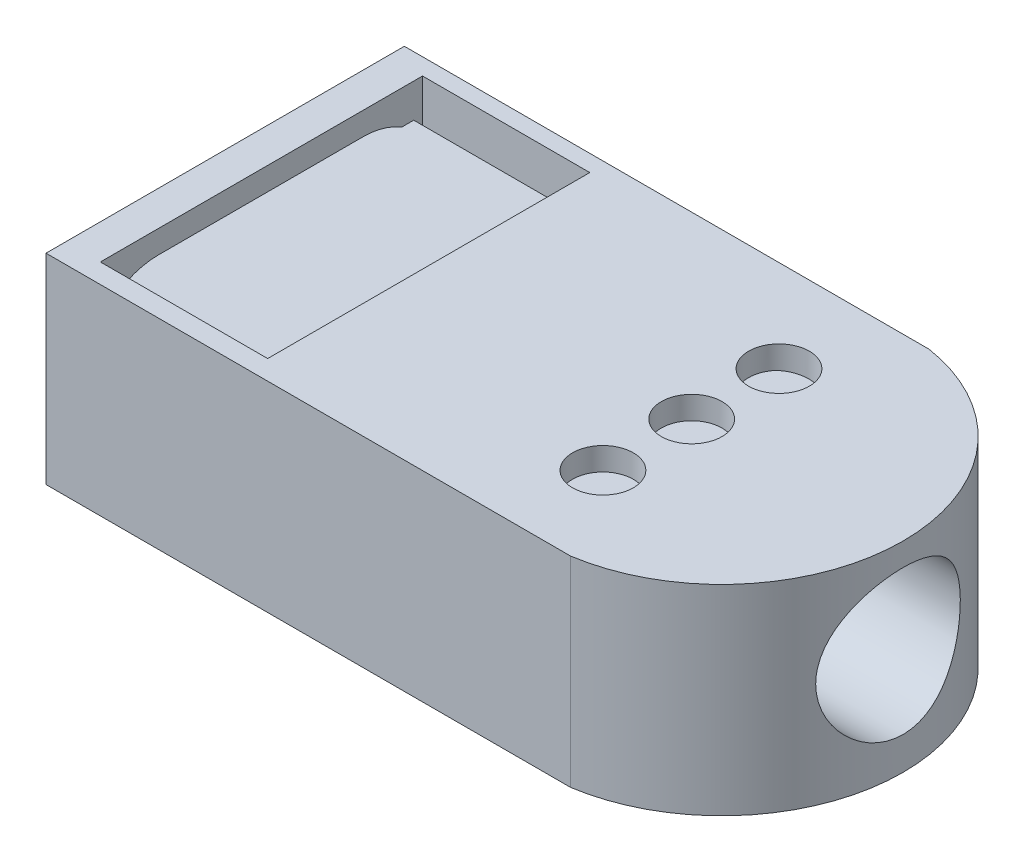
SolidWorks part; units mm, degrees
ref_plane "Front" through (0, 0, 0) normal (0, 0, 1) x (1, 0, 0)
ref_plane "Top" through (0, 0, 0) normal (0, 1, 0) x (1, 0, 0)
ref_plane "Right" through (0, 0, 0) normal (1, 0, 0) x (0, 0, -1)
sketch "草图4" plane through (0, 0, 0) normal (0, 1, 0) x (1, 0, 0)
  line L1 (25.3714, -17.8848) -> (-25.3714, -17.8848)
  line L2 (25.3714, -17.8848) -> (25.3714, 17.8848)
  line L3 (25.3714, 17.8848) -> (-25.3714, 17.8848)
  line L4 (-25.3714, -17.8848) -> (-25.3714, 17.8848)
  line L5 (25.3714, -17.8848) -> (-25.3714, 17.8848) construction
  line L6 (25.3714, 17.8848) -> (-25.3714, -17.8848) construction
  arc A0 (25.3714, 17.8848) -> (25.3714, -17.8848) centre (22.5519, 0) cw
  point P0 (0, 0)
  dimension "D3" = 18.1057
  dimension "D1" = 35.7696
  dimension "D2" = 50.7429
extrude "凸台-拉伸3" add sketch "草图4" along normal blind 20 contours L4 L1 L2 L3 | A0 L2
sketch "草图5" plane through (-25.3714, 0, 0) normal (-1, 0, 0) x (0, 0, 1)
  line L0 (-10.3143, 10.5325) -> (10.1565, 10.5325) construction
  line L1 (-10.3143, 17.7111) -> (10.1565, 17.7111)
  line L2 (-10.3143, 3.3539) -> (10.1565, 3.3539)
  arc A0 (-10.3143, 17.7111) -> (-10.3143, 3.3539) centre (-10.3143, 10.5325) ccw
  arc A1 (10.1565, 3.3539) -> (10.1565, 17.7111) centre (10.1565, 10.5325) ccw
  point P2 (-0.0789, 10.5325)
extrude "切除-拉伸1" cut sketch "草图5" against normal blind 48 contours L1 A1 L2 A0
sketch "草图6" plane through (-25.3714, 0, 0) normal (-1, 0, 0) x (0, 0, 1)
  circle A0 centre (0, 10.493) radius 7.2169
extrude "切除-拉伸2" cut sketch "草图6" against normal blind 68 contours A0
sketch "草图7" plane through (0, 20, 0) normal (0, 1, 0) x (1, 0, 0)
  line L1 (-23.5255, 16.2222) -> (-6.8293, 16.2222)
  line L2 (-23.5255, 16.2222) -> (-23.5255, -15.9306)
  line L3 (-23.5255, -15.9306) -> (-6.8293, -15.9306)
  line L4 (-6.8293, 16.2222) -> (-6.8293, -15.9306)
  circle A0 centre (17.8868, 10.3895) radius 4.1756
  circle A1 centre (17.8868, 0) radius 4.1502
  circle A2 centre (17.8868, -10.3166) radius 4.0443
extrude "切除-拉伸4" cut sketch "草图7" against normal blind 5 contours L2 L3 L4 L1
sketch "草图8" plane through (0, 20, 0) normal (0, 1, 0) x (1, 0, 0)
  circle A0 centre (19.5637, 0) radius 3.0292
  circle A1 centre (19.5637, 8.7126) radius 3.03
  circle A2 centre (19.5637, -8.8584) radius 3.0308
  dimension "D1" = 6.0585
  dimension "D2" = 6.06
  dimension "D4" = 6.0617
  dimension "D3" = 8.7126
extrude "切除-拉伸5" cut sketch "草图8" against normal blind 3 contours A2 | A1 | A0
sketch "草图9" plane through (-25.3714, 0, 0) normal (-1, 0, 0) x (0, 0, 1)
  line L0 (-10.3143, 17.7111) -> (10.1565, 17.7111) construction
  line L1 (-10.3143, 3.3539) -> (-1.0563, 3.3539) construction
  line L2 (-10.3143, 17.7111) -> (-10.3143, 3.3539) construction
  line L3 (-17.8848, 20) -> (-17.8848, 0) construction
  line L4 (-15.3444, 16.6157) -> (-10.3143, 16.6157)
  line L5 (-15.3444, 16.6157) -> (-15.3444, 15.9837)
  line L6 (-15.3444, 15.9837) -> (-10.3143, 15.9837)
  line L7 (-10.3143, 16.6157) -> (-10.3143, 15.9837)
  line L8 (-17.4929, 14.2854) -> (-10.3143, 14.2854)
  line L9 (-17.4929, 14.2854) -> (-17.4929, 13.5744)
  line L10 (-17.4929, 13.5744) -> (-10.3143, 13.5744)
  line L11 (-10.3143, 14.2854) -> (-10.3143, 13.5744)
  line L12 (-17.8848, 11.0467) -> (-10.3143, 11.0467)
  line L13 (-17.8848, 11.0467) -> (-17.8848, 11.7576)
  line L14 (-17.8848, 11.7576) -> (-10.3143, 11.7576)
  line L15 (-10.3143, 11.0467) -> (-10.3143, 11.7576)
  dimension "D1" = 14.3572
extrude "凸台-拉伸5" add sketch "草图9" against normal blind 48
sketch "草图10" plane through (-25.3714, 0, 0) normal (-1, 0, 0) x (0, 0, 1)
  line L2 (-10.3143, 11.7576) -> (17.3177, 11.7576)
  line L3 (-10.3143, 11.7576) -> (-10.3143, 11.0328)
  line L4 (-10.3143, 11.0328) -> (17.3177, 11.0328)
  line L5 (17.3177, 11.7576) -> (17.3177, 11.0328)
  line L6 (-10.3143, 14.2854) -> (17.3177, 14.2854)
  line L7 (-10.3143, 14.2854) -> (-10.3143, 13.5744)
  line L8 (-10.3143, 13.5744) -> (17.3177, 13.5744)
  line L9 (17.3177, 14.2854) -> (17.3177, 13.5744)
  line L10 (-10.3143, 16.6157) -> (17.3177, 16.6157)
  line L11 (-10.3143, 16.6157) -> (-10.3143, 15.9837)
  line L12 (-10.3143, 15.9837) -> (17.3177, 15.9837)
  line L13 (17.3177, 16.6157) -> (17.3177, 15.9837)
  arc A0 (10.1565, 3.3539) -> (10.1565, 17.7111) centre (10.1565, 10.5325) ccw construction
extrude "凸台-拉伸6" add sketch "草图10" against normal blind 48
sketch "草图12" plane through (-25.3714, 0, 0) normal (-1, 0, 0) x (0, 0, 1)
  line L1 (-17.8848, 20) -> (17.8848, 20)
  line L2 (-17.8848, 20) -> (-17.8848, 0)
  line L3 (-17.8848, 0) -> (17.8848, 0)
  line L4 (17.8848, 20) -> (17.8848, 0)
  line L5 (-0.6526, 20) -> (0.6526, 20)
  line L6 (-0.6526, 20) -> (-0.6526, 20.6193)
  line L7 (-0.6526, 20.6193) -> (0.6526, 20.6193)
  line L8 (0.6526, 20) -> (0.6526, 20.6193)
sketch "草图13" plane through (0, 20, 0) normal (0, 1, 0) x (1, 0, 0)
  line L0 (-25.3714, 17.8848) -> (-25.3714, -17.8848) construction
  line L1 (-26.9993, 17.8848) -> (-25.3714, 17.8848)
  line L2 (-26.9993, 17.8848) -> (-26.9993, -17.8848)
  line L3 (-26.9993, -17.8848) -> (-25.3714, -17.8848)
  line L4 (-25.3714, 17.8848) -> (-25.3714, -17.8848)
  line L5 (25.3714, -17.8848) -> (-25.3714, -17.8848) construction
extrude "凸台-拉伸9" add sketch "草图13" against normal blind 20
sketch "草图15" plane through (0, 20, 0) normal (0, 1, 0) x (1, 0, 0)
  line L0 (-26.9993, 17.8848) -> (-26.9993, -17.8848) construction
  line L1 (-26.9993, 16.1211) -> (-25.3714, 16.1211)
  line L2 (-26.9993, 16.1211) -> (-26.9993, -15.9715)
  line L3 (-26.9993, -15.9715) -> (-25.3714, -15.9715)
  line L4 (-25.3714, 16.1211) -> (-25.3714, -15.9715)
  line L5 (-25.3714, 17.8848) -> (-25.3714, -17.8848) construction
extrude "凸台-拉伸11" add sketch "草图15" against normal through all
scale "缩放比例1" scale about centroid uniform scaling yes scale factor 2.16174
